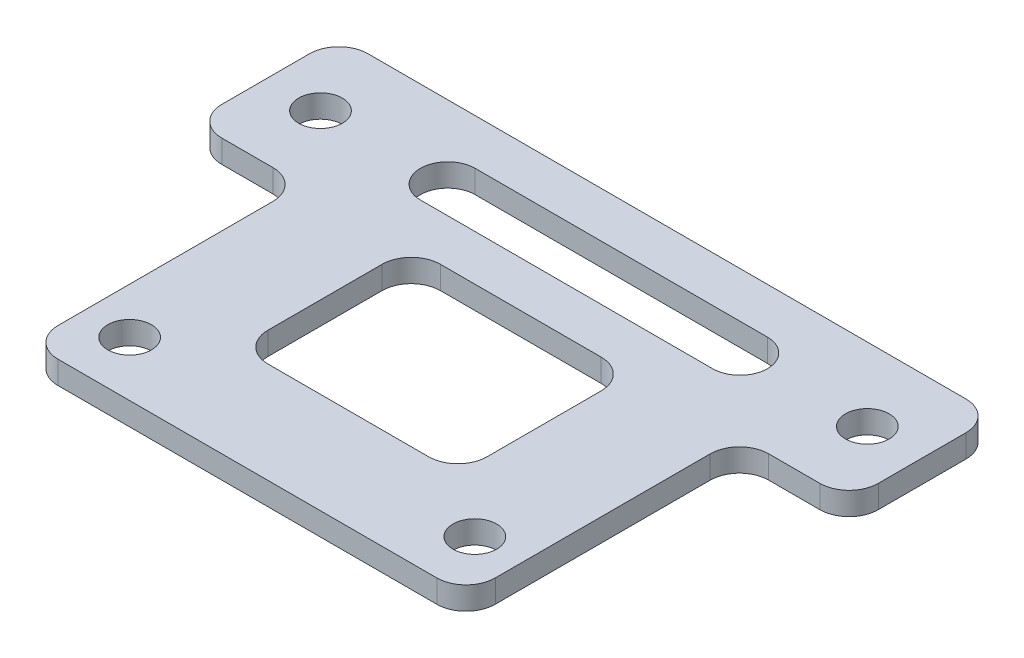
SolidWorks part; units mm, degrees
ref_plane "Front Plane" through (0, 0, 0) normal (0, 0, 1) x (1, 0, 0)
ref_plane "Top Plane" through (0, 0, 0) normal (0, 1, 0) x (1, 0, 0)
ref_plane "Right Plane" through (0, 0, 0) normal (1, 0, 0) x (0, 0, -1)
sketch "Sketch2" plane through (0, 0, 0) normal (0, 1, 0) x (1, 0, 0)
  line L0 (0, 0) -> (0, 23.7625)
  line L1 (0, 36.4625) -> (38, 36.4625)
  line L2 (38, 23.7625) -> (38, 0)
  line L3 (38, 0) -> (27.0552, 0)
  line L5 (28.525, 23.7625) -> (9.475, 23.7625)
  line L7 (27.0552, 0) -> (0, 0)
  line L8 (4, 4.7625) -> (34, 4.7625) construction
  line L9 (19, 23.7625) -> (19, 36.4625) construction
  line L10 (0, 30.1125) -> (38, 30.1125) construction
  line L11 (6.3, 30.1125) -> (31.7, 30.1125) construction
  line L12 (6.3, 32.4938) -> (31.7, 32.4938)
  line L13 (6.3, 27.7313) -> (31.7, 27.7313)
  line L14 (9.475, 23.7625) -> (9.475, 8.7625)
  line L15 (9.475, 8.7625) -> (28.525, 8.7625)
  line L16 (28.525, 8.7625) -> (28.525, 23.7625)
  line L17 (0, 23.7625) -> (-9.525, 23.7625)
  line L18 (-9.525, 23.7625) -> (-9.525, 36.4625)
  line L19 (-9.525, 36.4625) -> (0, 36.4625)
  line L20 (38, 23.7625) -> (47.525, 23.7625)
  line L21 (47.525, 23.7625) -> (47.525, 36.4625)
  line L22 (47.525, 36.4625) -> (38, 36.4625)
  line L23 (42.7625, 23.7625) -> (42.7625, 36.4625) construction
  line L24 (-4.7625, 23.7625) -> (-4.7625, 36.4625) construction
  circle A0 centre (34, 4.7625) radius 1.8986
  circle A1 centre (4, 4.7625) radius 1.8987
  circle A2 centre (-4.7625, 30.1125) radius 1.8987
  circle A3 centre (42.7625, 30.1125) radius 1.8986
  arc A4 (6.3, 32.4938) -> (6.3, 27.7313) centre (6.3, 30.1125) ccw
  arc A5 (31.7, 27.7313) -> (31.7, 32.4938) centre (31.7, 30.1125) ccw
  point P13 (19, 4.7625)
  point P14 (19, 23.7625)
  point P19 (19, 30.1125)
  point P24 (19, 30.1125)
  point P31 (19, 32.4938)
  point P41 (42.7625, 36.4625)
  dimension "D5" = 3.7973
  dimension "D1" = 15
  dimension "D2" = 12.7
  dimension "D3" = 38
  dimension "D4" = 38
  dimension "D6" = 30
  dimension "D7" = 4.7625
  dimension "D8" = 25.4
  dimension "D9" = 4.7625
  dimension "D10" = 19.05
  dimension "D11" = 4
  dimension "D12" = 9.525
extrude "Boss-Extrude1" add sketch "Sketch2" along normal blind 1.9844
fillet "Fillet1" radius 2.54 12 edges at (0, 0.9922, 0) (38, 0.9922, 0) (9.475, 0.9922, -8.7625) (9.475, 0.9922, -23.7625) (28.525, 0.9922, -8.7625) (28.525, 0.9922, -23.7625) (47.525, 0.9922, -36.4625) (47.525, 0.9922, -23.7625) (38, 0.9922, -23.7625) (-9.525, 0.9922, -36.4625) (-9.525, 0.9922, -23.7625) (0, 0.9922, -23.7625)
